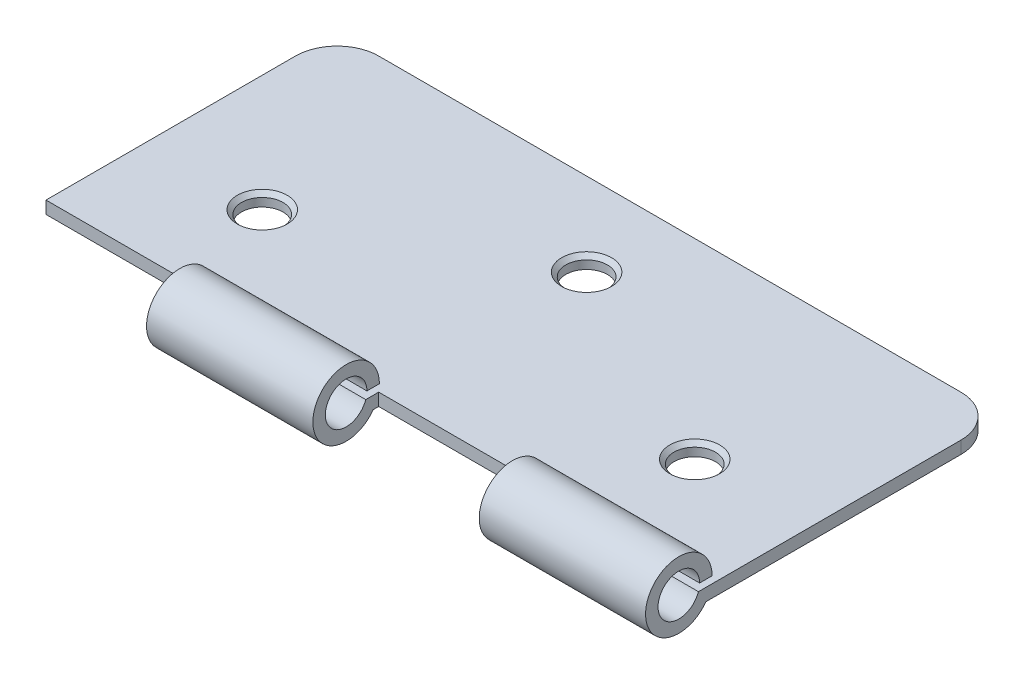
SolidWorks part; units mm, degrees
material "Brass"
ref_plane "Front Plane" through (0, 0, 0) normal (0, 0, 1) x (1, 0, 0)
ref_plane "Top Plane" through (0, 0, 0) normal (0, 1, 0) x (1, 0, 0)
ref_plane "Right Plane" through (0, 0, 0) normal (1, 0, 0) x (0, 0, -1)
sketch "Sketch1" plane through (0, 0, 0) normal (0, 1, 0) x (1, 0, 0)
  line L1 (-35, 17.5) -> (35, 17.5)
  line L2 (-40, 12.5) -> (-40, -17.5)
  line L3 (-40, -17.5) -> (40, -17.5)
  line L4 (40, 12.5) -> (40, -17.5)
  line L5 (-40, 17.5) -> (40, -17.5) construction
  line L6 (-40, -17.5) -> (40, 17.5) construction
  arc A0 (35, 17.5) -> (40, 12.5) centre (35, 12.5) cw
  arc A1 (-35, 17.5) -> (-40, 12.5) centre (-35, 12.5) ccw
  point P0 (0, 0)
  dimension "D3" = 5
  dimension "D1" = 80
  dimension "D2" = 35
extrude "Boss-Extrude1" add sketch "Sketch1" along normal blind 1.5
sketch "Sketch2" plane through (40, 0, 0) normal (1, 0, 0) x (0, 0, -1)
  line L0 (-17.5, 0) -> (-18.1615, 0)
  line L1 (-17.5, 1.5) -> (-19.0547, 1.5)
  line L2 (-18.913, 2.3298) -> (-17.413, 2.3298)
  line L3 (-17.5, 0) -> (-17.5, 1.5)
  arc A0 (-17.413, 2.3298) -> (-18.1615, 0) centre (-21.413, 2.3298) ccw
  arc A1 (-18.913, 2.3298) -> (-19.0547, 1.5) centre (-21.413, 2.3298) ccw
  dimension "D1" = 8
  dimension "D2" = 5
extrude "Boss-Extrude3" add sketch "Sketch2" against normal blind 20
pattern_linear "LPattern1" count 2 spacing 40 along (-1, 0, 0) of "Boss-Extrude3"
sketch "Sketch3" plane through (0, 1.5, 0) normal (0, 1, 0) x (1, 0, 0)
  line L0 (-40, -17.5) -> (-20, -17.5) construction
  line L1 (0, -17.5) -> (20, -17.5) construction
  line L2 (40, -19.0547) -> (40, 12.5) construction
  line L3 (-40, 12.5) -> (-40, -17.5) construction
  line L4 (35, 17.5) -> (-35, 17.5) construction
  circle A0 centre (0, 7.5) radius 2.5
  circle A1 centre (-26, -5.5) radius 2.5
  circle A2 centre (26, -5.5) radius 2.5
  point P17 (0, 0)
  dimension "D1" = 5
  dimension "D2" = 5
  dimension "D3" = 5
  dimension "D4" = 12
  dimension "D5" = 12
  dimension "D6" = 14
  dimension "D7" = 14
  dimension "D8" = 10
extrude "Cut-Extrude1" cut sketch "Sketch3" against normal blind 20
chamfer "Chamfer1" distance 0.5 angle 45 3 edges at (-26, 1.5, 8) (0, 1.5, -5) (26, 1.5, 8)
